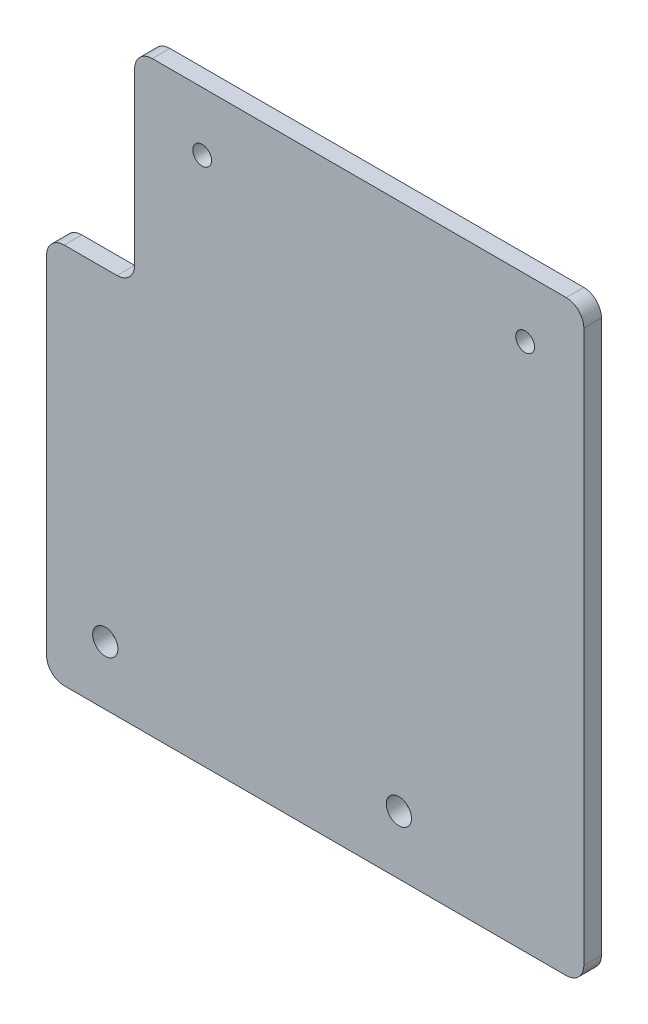
SolidWorks part; units mm, degrees
material "6061-T6 (SS)"
ref_plane "Front Plane" through (0, 0, 0) normal (0, 0, 1) x (1, 0, 0)
ref_plane "Top Plane" through (0, 0, 0) normal (0, 1, 0) x (1, 0, 0)
ref_plane "Right Plane" through (0, 0, 0) normal (1, 0, 0) x (0, 0, -1)
sketch "Sketch1" plane through (0, 0, 0) normal (0, 0, 1) x (1, 0, 0)
  line L0 (25, 0) -> (-25, 0) construction
  line L1 (-8.5, 0) -> (-8.5, 80) construction
  line L2 (-8.5, 80) -> (46.5, 80) construction
  line L4 (56.5, -10) -> (-35, -10)
  line L5 (56.5, -10) -> (56.5, 90)
  line L6 (56.5, 90) -> (-35, 90)
  line L7 (-35, -10) -> (-35, 90)
  line L8 (56.5, -10) -> (-35, 90) construction
  line L9 (56.5, 90) -> (-35, -10) construction
  point P4 (0, 0)
  point P7 (10.75, 40)
  dimension "D1" = 80
  dimension "D2" = 16.5
  dimension "D3" = 55
  dimension "D4" = 50
  dimension "D5" = 10
  dimension "D6" = 10
  dimension "D7" = 10
  dimension "D8" = 10
extrude "Boss-Extrude1" add sketch "Sketch1" along normal blind 3
hole_wizard "M4 Clearance Hole1" positions "Sketch2" profile "Sketch3" hole size "M4" standard "ANSI Metric" end condition through all
sketch "Sketch2" plane through (0, 0, 3) normal (0, 0, 1) x (1, 0, 0)
  point P0 (-25, 0)
  point P3 (25, 0)
sketch "Sketch3" plane through (-25, 0, 3) normal (1, 0, 0) x (0, -1, 0)
  line L0 (0, 0) -> (0, 3)
  line L1 (0, 3) -> (2.15, 3)
  line L2 (2.15, 3) -> (2.15, 0)
  line L5 (2.15, 0) -> (0, 0)
  line L11 (0, -6.35) -> (0, 107.95) construction
  dimension "Thru Hole Dia." = 4.3
  dimension "Thru Hole Depth" = 3
hole_wizard "M3 Clearance Hole1" positions "Sketch4" profile "Sketch5" hole size "M3" standard "ANSI Metric" end condition through all
sketch "Sketch4" plane through (0, 0, 3) normal (0, 0, 1) x (1, 0, 0)
  point P0 (-8.5, 80)
  point P3 (46.5, 80)
sketch "Sketch5" plane through (-8.5, 80, 3) normal (1, 0, 0) x (0, -1, 0)
  line L0 (0, 0) -> (0, 3)
  line L1 (0, 3) -> (1.6, 3)
  line L2 (1.6, 3) -> (1.6, 0)
  line L5 (1.6, 0) -> (0, 0)
  line L11 (0, -6.35) -> (0, 107.95) construction
  dimension "Thru Hole Dia." = 3.2
  dimension "Thru Hole Depth" = 3
sketch "Sketch6" plane through (0, 0, 3) normal (0, 0, 1) x (1, 0, 0)
  line L0 (56.5, 90) -> (-35, 90) construction
  line L1 (-20, 90) -> (-35, 90)
  line L2 (-20, 90) -> (-20, 55)
  line L3 (-20, 55) -> (-35, 55)
  line L4 (-35, 90) -> (-35, 55)
  line L5 (-35, 90) -> (-35, -10) construction
  dimension "D1" = 35
  dimension "D2" = 15
extrude "Cut-Extrude1" cut sketch "Sketch6" against normal through all
fillet "Fillet1" radius 3 6 edges at (56.5, 90, 1.5) (56.5, -10, 1.5) (-35, -10, 1.5) (-20, 90, 1.5) (-20, 55, 1.5) (-35, 55, 1.5)
